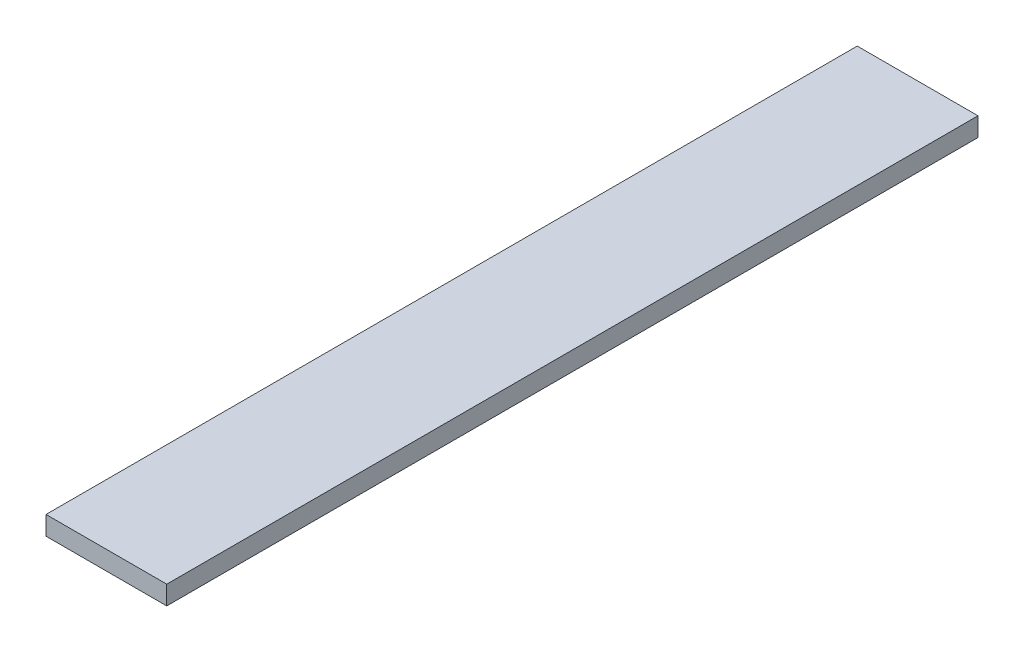
SolidWorks part; units mm, degrees
ref_plane "Plano frontal" through (0, 0, 0) normal (0, 0, 1) x (1, 0, 0)
ref_plane "Plano superior" through (0, 0, 0) normal (0, 1, 0) x (1, 0, 0)
ref_plane "Plano direito" through (0, 0, 0) normal (1, 0, 0) x (0, 0, -1)
sketch "Esboço1" plane through (0, 0, 0) normal (0, 0, 1) x (1, 0, 0)
  line L1 (48, 7.5) -> (-48, 7.5)
  line L2 (48, 7.5) -> (48, -7.5)
  line L3 (48, -7.5) -> (-48, -7.5)
  line L4 (-48, 7.5) -> (-48, -7.5)
  line L5 (48, 7.5) -> (-48, -7.5) construction
  line L6 (48, -7.5) -> (-48, 7.5) construction
  point P0 (0, 0)
  dimension "D1" = 96
  dimension "D2" = 15
extrude "Ressalto-extrusão1" add sketch "Esboço1" along normal blind 645
